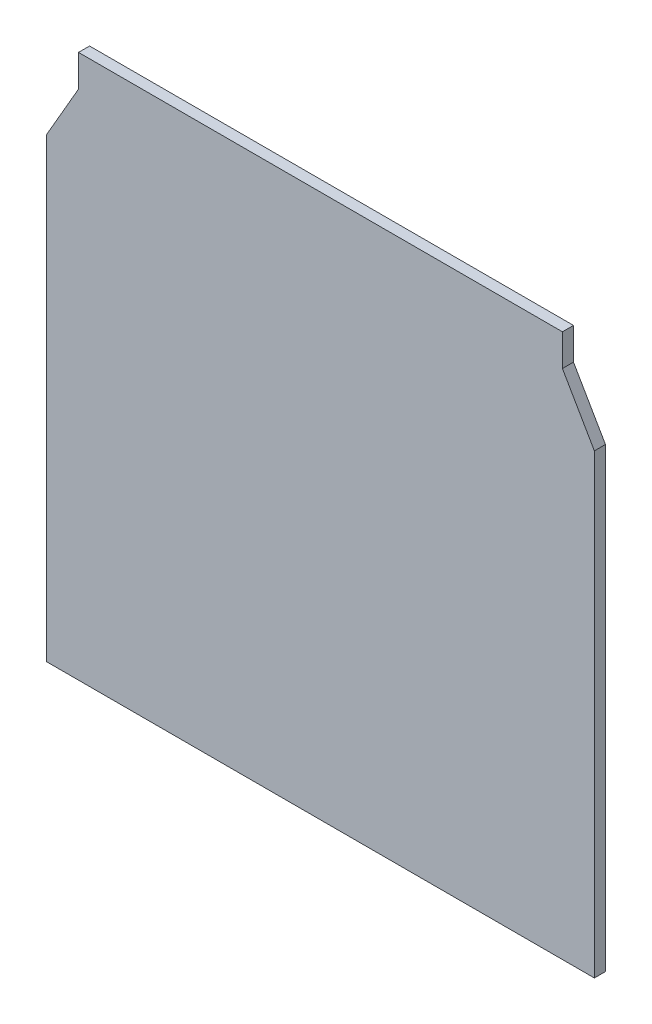
SolidWorks part; units mm, degrees
ref_plane "前视基准面" through (0, 0, 0) normal (0, 0, 1) x (1, 0, 0)
ref_plane "上视基准面" through (0, 0, 0) normal (0, 1, 0) x (1, 0, 0)
ref_plane "右视基准面" through (0, 0, 0) normal (1, 0, 0) x (0, 0, -1)
other "Configuration Table"
sketch "草图1" plane through (0, 0, 0) normal (0, 0, 1) x (1, 0, 0)
  line L0 (-99, 0) -> (99, 0)
  line L1 (99, 0) -> (99, 165)
  line L2 (-99, 0) -> (-99, 165)
  line L3 (-99, 165) -> (99, 165) construction
  line L4 (99, 165) -> (87.453, 185)
  line L5 (-99, 165) -> (-87.453, 185)
  line L6 (-87.453, 185) -> (-87.453, 196.5)
  line L7 (87.453, 185) -> (87.453, 196.5)
  line L8 (-87.453, 196.5) -> (87.453, 196.5)
  dimension "D1" = 198
  dimension "D2" = 165
  dimension "D3" = 60
  dimension "D4" = 60
  dimension "D5" = 20
  dimension "D6" = 20
  dimension "D7" = 11.5
extrude "凸台-拉伸1" add sketch "草图1" along normal blind 4
